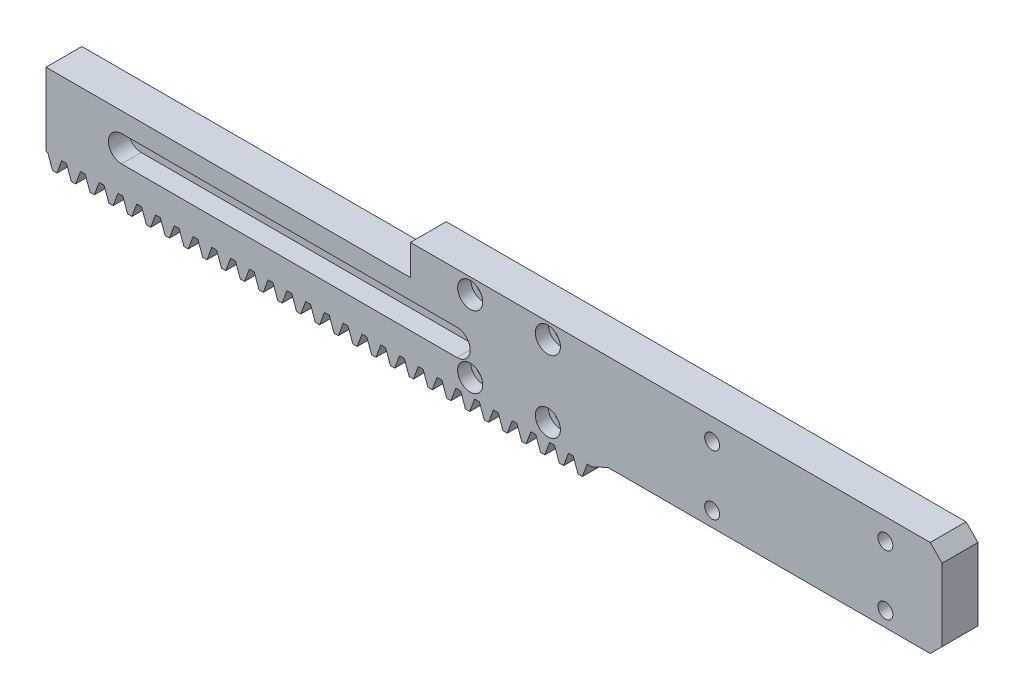
SolidWorks part; units mm, degrees
ref_plane "前视基准面" through (0, 0, 0) normal (0, 0, 1) x (1, 0, 0)
ref_plane "上视基准面" through (0, 0, 0) normal (0, 1, 0) x (1, 0, 0)
ref_plane "右视基准面" through (0, 0, 0) normal (1, 0, 0) x (0, 0, -1)
other "Configuration Table"
sketch "Module 1 rack with vertical carrier tail profile" plane through (0, 0, 0) normal (0, 0, 1) x (1, 0, 0)
  line L0 (-69, 10.26) -> (-68.7132, 10.26)
  line L1 (-68.7132, 10.26) -> (-67.9089, 8.05)
  line L2 (-67.9089, 8.05) -> (-67.1796, 8.05)
  line L3 (-67.1796, 8.05) -> (-66.3752, 10.26)
  line L4 (-66.3752, 10.26) -> (-65.5717, 10.26)
  line L5 (-65.5717, 10.26) -> (-64.7673, 8.05)
  line L6 (-64.7673, 8.05) -> (-64.038, 8.05)
  line L7 (-64.038, 8.05) -> (-63.2336, 10.26)
  line L8 (-63.2336, 10.26) -> (-62.4301, 10.26)
  line L9 (-62.4301, 10.26) -> (-61.6257, 8.05)
  line L10 (-61.6257, 8.05) -> (-60.8964, 8.05)
  line L11 (-60.8964, 8.05) -> (-60.0921, 10.26)
  line L12 (-60.0921, 10.26) -> (-59.2885, 10.26)
  line L13 (-59.2885, 10.26) -> (-58.4841, 8.05)
  line L14 (-58.4841, 8.05) -> (-57.7548, 8.05)
  line L15 (-57.7548, 8.05) -> (-56.9505, 10.26)
  line L16 (-56.9505, 10.26) -> (-56.1469, 10.26)
  line L17 (-56.1469, 10.26) -> (-55.3425, 8.05)
  line L18 (-55.3425, 8.05) -> (-54.6132, 8.05)
  line L19 (-54.6132, 8.05) -> (-53.8089, 10.26)
  line L20 (-53.8089, 10.26) -> (-53.0053, 10.26)
  line L21 (-53.0053, 10.26) -> (-52.2009, 8.05)
  line L22 (-52.2009, 8.05) -> (-51.4717, 8.05)
  line L23 (-51.4717, 8.05) -> (-50.6673, 10.26)
  line L24 (-50.6673, 10.26) -> (-49.8637, 10.26)
  line L25 (-49.8637, 10.26) -> (-49.0593, 8.05)
  line L26 (-49.0593, 8.05) -> (-48.3301, 8.05)
  line L27 (-48.3301, 8.05) -> (-47.5257, 10.26)
  line L28 (-47.5257, 10.26) -> (-46.7221, 10.26)
  line L29 (-46.7221, 10.26) -> (-45.9177, 8.05)
  line L30 (-45.9177, 8.05) -> (-45.1885, 8.05)
  line L31 (-45.1885, 8.05) -> (-44.3841, 10.26)
  line L32 (-44.3841, 10.26) -> (-43.5805, 10.26)
  line L33 (-43.5805, 10.26) -> (-42.7761, 8.05)
  line L34 (-42.7761, 8.05) -> (-42.0469, 8.05)
  line L35 (-42.0469, 8.05) -> (-41.2425, 10.26)
  line L36 (-41.2425, 10.26) -> (-40.4389, 10.26)
  line L37 (-40.4389, 10.26) -> (-39.6345, 8.05)
  line L38 (-39.6345, 8.05) -> (-38.9053, 8.05)
  line L39 (-38.9053, 8.05) -> (-38.1009, 10.26)
  line L40 (-38.1009, 10.26) -> (-37.2973, 10.26)
  line L41 (-37.2973, 10.26) -> (-36.4929, 8.05)
  line L42 (-36.4929, 8.05) -> (-35.7637, 8.05)
  line L43 (-35.7637, 8.05) -> (-34.9593, 10.26)
  line L44 (-34.9593, 10.26) -> (-34.1557, 10.26)
  line L45 (-34.1557, 10.26) -> (-33.3513, 8.05)
  line L46 (-33.3513, 8.05) -> (-32.6221, 8.05)
  line L47 (-32.6221, 8.05) -> (-31.8177, 10.26)
  line L48 (-31.8177, 10.26) -> (-31.0141, 10.26)
  line L49 (-31.0141, 10.26) -> (-30.2098, 8.05)
  line L50 (-30.2098, 8.05) -> (-29.4805, 8.05)
  line L51 (-29.4805, 8.05) -> (-28.6761, 10.26)
  line L52 (-28.6761, 10.26) -> (-27.8725, 10.26)
  line L53 (-27.8725, 10.26) -> (-27.0682, 8.05)
  line L54 (-27.0682, 8.05) -> (-26.3389, 8.05)
  line L55 (-26.3389, 8.05) -> (-25.5345, 10.26)
  line L56 (-25.5345, 10.26) -> (-24.7309, 10.26)
  line L57 (-24.7309, 10.26) -> (-23.9266, 8.05)
  line L58 (-23.9266, 8.05) -> (-23.1973, 8.05)
  line L59 (-23.1973, 8.05) -> (-22.3929, 10.26)
  line L60 (-22.3929, 10.26) -> (-21.5894, 10.26)
  line L61 (-21.5894, 10.26) -> (-20.785, 8.05)
  line L62 (-20.785, 8.05) -> (-20.0557, 8.05)
  line L63 (-20.0557, 8.05) -> (-19.2514, 10.26)
  line L64 (-19.2514, 10.26) -> (-18.4478, 10.26)
  line L65 (-18.4478, 10.26) -> (-17.6434, 8.05)
  line L66 (-17.6434, 8.05) -> (-16.9141, 8.05)
  line L67 (-16.9141, 8.05) -> (-16.1098, 10.26)
  line L68 (-16.1098, 10.26) -> (-15.3062, 10.26)
  line L69 (-15.3062, 10.26) -> (-14.5018, 8.05)
  line L70 (-14.5018, 8.05) -> (-13.7725, 8.05)
  line L71 (-13.7725, 8.05) -> (-12.9682, 10.26)
  line L72 (-12.9682, 10.26) -> (-12.1646, 10.26)
  line L73 (-12.1646, 10.26) -> (-11.3602, 8.05)
  line L74 (-11.3602, 8.05) -> (-10.6309, 8.05)
  line L75 (-10.6309, 8.05) -> (-9.8266, 10.26)
  line L76 (-9.8266, 10.26) -> (-9.023, 10.26)
  line L77 (-9.023, 10.26) -> (-8.2186, 8.05)
  line L78 (-8.2186, 8.05) -> (-7.4894, 8.05)
  line L79 (-7.4894, 8.05) -> (-6.685, 10.26)
  line L80 (-6.685, 10.26) -> (-5.8814, 10.26)
  line L81 (-5.8814, 10.26) -> (-5.077, 8.05)
  line L82 (-5.077, 8.05) -> (-4.3478, 8.05)
  line L83 (-4.3478, 8.05) -> (-3.5434, 10.26)
  line L84 (-3.5434, 10.26) -> (-2.7398, 10.26)
  line L85 (-2.7398, 10.26) -> (-1.9354, 8.05)
  line L86 (-1.9354, 8.05) -> (-1.2062, 8.05)
  line L87 (-1.2062, 8.05) -> (-0.4018, 10.26)
  line L88 (-0.4018, 10.26) -> (0.4018, 10.26)
  line L89 (0.4018, 10.26) -> (1.2062, 8.05)
  line L90 (1.2062, 8.05) -> (1.9354, 8.05)
  line L91 (1.9354, 8.05) -> (2.7398, 10.26)
  line L92 (2.7398, 10.26) -> (3.5434, 10.26)
  line L93 (3.5434, 10.26) -> (4.3478, 8.05)
  line L94 (4.3478, 8.05) -> (5.077, 8.05)
  line L95 (5.077, 8.05) -> (5.8814, 10.26)
  line L96 (5.8814, 10.26) -> (6.685, 10.26)
  line L97 (6.685, 10.26) -> (7.4894, 8.05)
  line L98 (7.4894, 8.05) -> (8.2186, 8.05)
  line L99 (8.2186, 8.05) -> (9.023, 10.26)
  line L100 (9.023, 10.26) -> (9.8266, 10.26)
  line L101 (9.8266, 10.26) -> (10.6309, 8.05)
  line L102 (10.6309, 8.05) -> (11.3602, 8.05)
  line L103 (11.3602, 8.05) -> (12.1646, 10.26)
  line L104 (12.1646, 10.26) -> (12.9682, 10.26)
  line L105 (12.9682, 10.26) -> (13.7725, 8.05)
  line L106 (13.7725, 8.05) -> (14.5018, 8.05)
  line L107 (14.5018, 8.05) -> (15.3062, 10.26)
  line L108 (15.3062, 10.26) -> (16.1098, 10.26)
  line L109 (16.1098, 10.26) -> (16.9141, 8.05)
  line L110 (16.9141, 8.05) -> (17.6434, 8.05)
  line L111 (17.6434, 8.05) -> (18.4478, 10.26)
  line L112 (18.4478, 10.26) -> (19.2514, 10.26)
  line L113 (19.2514, 10.26) -> (20.0557, 8.05)
  line L114 (20.0557, 8.05) -> (20.785, 8.05)
  line L115 (20.785, 8.05) -> (21.5894, 10.26)
  line L116 (21.5894, 10.26) -> (22.5, 10.26)
  line L117 (22.5, 10.26) -> (25, 11.5)
  line L118 (25, 11.5) -> (79, 11.5)
  line L119 (79, 11.5) -> (81, 13.5)
  line L120 (81, 13.5) -> (81, 25.6)
  line L121 (81, 25.6) -> (79, 27.6)
  line L122 (79, 27.6) -> (22.5, 27.6)
  line L123 (22.5, 27.6) -> (22.5, 22.5)
  line L124 (22.5, 22.5) -> (-69, 22.5)
  line L125 (-69, 22.5) -> (-69, 10.26)
extrude "Module 1 rack with vertical carrier tail" add sketch "Module 1 rack with vertical carrier tail profile" along normal blind 6 from offset 40.4
sketch "MGN7H carriage fixing pad profile" plane through (0, 0, 0) normal (0, 0, 1) x (1, 0, 0)
  line L0 (-8, 21.5) -> (25, 21.5)
  line L1 (25, 21.5) -> (25, 27.6)
  line L2 (25, 27.6) -> (-8, 27.6)
  line L3 (-8, 27.6) -> (-8, 21.5)
extrude "MGN7H carriage fixing pad" add sketch "MGN7H carriage fixing pad profile" along normal blind 6 from offset 40.4
sketch "Full stroke limit slot 56.55 mm profile" plane through (0, 0, 0) normal (0, 0, 1) x (1, 0, 0)
  line L0 (-56.3487, 14.8) -> (-0.2, 14.8)
  line L1 (-0.2, 19.2) -> (-56.3487, 19.2)
  arc A0 (-0.2, 14.8) -> (-0.2, 19.2) centre (-0.2, 17) ccw
  arc A1 (-56.3487, 19.2) -> (-56.3487, 14.8) centre (-56.3487, 17) ccw
extrude "Full stroke limit slot 56.55 mm" cut sketch "Full stroke limit slot 56.55 mm profile" along normal blind 3.4 from offset 43.1
sketch "Radar seat four M3 pilots 29 x 10 mm profile" plane through (0, 0, 0) normal (0, 0, 1) x (1, 0, 0)
  circle A0 centre (42.5, 14) radius 1.25
  circle A1 centre (42.5, 24) radius 1.25
  circle A2 centre (71.5, 14) radius 1.25
  circle A3 centre (71.5, 24) radius 1.25
  point P8 (26.5, 11)
  dimension "D3" = 2.5
  dimension "D6" = 2.5
  dimension "D9" = 2.5
  dimension "D12" = 2.5
  dimension "D1" = 16
  dimension "D2" = 3
  dimension "D4" = 16
  dimension "D5" = 13
  dimension "D7" = 45
  dimension "D8" = 3
  dimension "D10" = 45
  dimension "D11" = 13
extrude "Radar seat four M3 pilots 29 x 10 mm" cut sketch "Radar seat four M3 pilots 29 x 10 mm profile" along normal blind 6.2 from offset 40.3
sketch "MGN7H four M2 clearances 13 x 12 mm profile" plane through (0, 0, 0) normal (0, 0, 1) x (1, 0, 0)
  circle A0 centre (2, 13) radius 1.1
  circle A1 centre (2, 25) radius 1.1
  circle A2 centre (15, 13) radius 1.1
  circle A3 centre (15, 25) radius 1.1
  point P8 (-8, 10)
  dimension "D3" = 2.2
  dimension "D6" = 2.2
  dimension "D9" = 2.2
  dimension "D12" = 2.2
  dimension "D1" = 10
  dimension "D2" = 3
  dimension "D4" = 10
  dimension "D5" = 15
  dimension "D7" = 23
  dimension "D8" = 3
  dimension "D10" = 23
  dimension "D11" = 15
extrude "MGN7H four M2 clearances 13 x 12 mm" cut sketch "MGN7H four M2 clearances 13 x 12 mm profile" along normal blind 6.2 from offset 40.3
sketch "MGN7H M2 head pockets profile" plane through (0, 0, 0) normal (0, 0, 1) x (1, 0, 0)
  circle A0 centre (2, 13) radius 2.1
  circle A1 centre (2, 25) radius 2.1
  circle A2 centre (15, 13) radius 2.1
  circle A3 centre (15, 25) radius 2.1
  point P8 (-8, 10)
  dimension "D3" = 4.2
  dimension "D6" = 4.2
  dimension "D9" = 4.2
  dimension "D12" = 4.2
  dimension "D1" = 10
  dimension "D2" = 3
  dimension "D4" = 10
  dimension "D5" = 15
  dimension "D7" = 23
  dimension "D8" = 3
  dimension "D10" = 23
  dimension "D11" = 15
extrude "MGN7H M2 head pockets" cut sketch "MGN7H M2 head pockets profile" along normal blind 2.3 from offset 44.2
